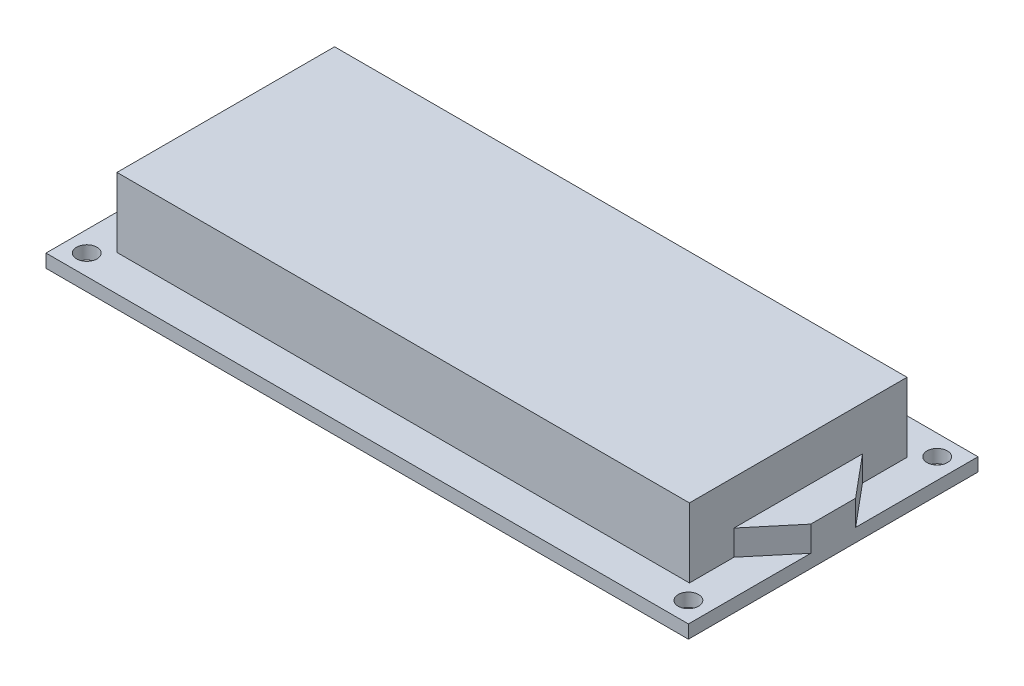
SolidWorks part; units mm, degrees
ref_plane "Front Plane" through (0, 0, 0) normal (0, 0, 1) x (1, 0, 0)
ref_plane "Top Plane" through (0, 0, 0) normal (0, 1, 0) x (1, 0, 0)
ref_plane "Right Plane" through (0, 0, 0) normal (1, 0, 0) x (0, 0, -1)
sketch "Sketch1" plane through (0, 0, 0) normal (0, 1, 0) x (1, 0, 0)
  line L1 (0, 14.1688) -> (80.01, 14.1688)
  line L2 (0, 14.1688) -> (0, 50.2368)
  line L3 (0, 50.2368) -> (80.01, 50.2368)
  line L4 (80.01, 14.1688) -> (80.01, 50.2368)
  dimension "D1" = 80.01
  dimension "D2" = 36.068
extrude "Boss-Extrude1" add sketch "Sketch1" along normal blind 1.651
sketch "Sketch2" plane through (0, 1.651, 0) normal (0, 1, 0) x (1, 0, 0)
  line L0 (0, 50.2368) -> (0, 14.1688) construction
  line L1 (80.01, 50.2368) -> (0, 50.2368) construction
  line L2 (0, 14.1688) -> (80.01, 14.1688) construction
  line L3 (80.01, 14.1688) -> (80.01, 50.2368) construction
  circle A0 centre (2.54, 47.6968) radius 1.27
  circle A1 centre (2.54, 16.7088) radius 1.27
  circle A2 centre (77.47, 47.6968) radius 1.27
  circle A3 centre (77.47, 16.7088) radius 1.27
  dimension "D1" = 2.54
  dimension "D2" = 2.54
  dimension "D3" = 2.54
  dimension "D4" = 2.54
  dimension "D5" = 2.54
extrude "Cut-Extrude1" cut sketch "Sketch2" against normal blind 2.54
sketch "Sketch3" plane through (0, 1.651, 0) normal (0, 1, 0) x (1, 0, 0)
  line L0 (80.01, 50.2368) -> (0, 50.2368) construction
  line L1 (4.3561, 45.7537) -> (75.6539, 45.7537)
  line L2 (4.3561, 45.7537) -> (4.3561, 18.6519)
  line L3 (4.3561, 18.6519) -> (75.6539, 18.6519)
  line L4 (75.6539, 45.7537) -> (75.6539, 18.6519)
  line L5 (0, 50.2368) -> (0, 14.1688) construction
  point P4 (40.005, 45.7537)
  point P7 (40.005, 50.2368)
  point P8 (4.3561, 32.2028)
  point P11 (0, 32.2028)
  dimension "D1" = 71.2978
  dimension "D2" = 27.1018
extrude "Boss-Extrude2" add sketch "Sketch3" along normal blind 8.636
sketch "Sketch4" plane through (0, 1.651, 0) normal (0, 1, 0) x (1, 0, 0)
  line L0 (4.3561, 40.2038) -> (0, 34.9968)
  line L1 (0, 34.9968) -> (0, 29.4088)
  line L2 (0, 29.4088) -> (4.3561, 24.2018)
  line L3 (4.3561, 24.2018) -> (4.3561, 40.2038)
  line L4 (4.3561, 45.7537) -> (4.3561, 18.6519) construction
  line L5 (0, 50.2368) -> (0, 14.1688) construction
  line L6 (0, 14.1688) -> (80.01, 14.1688) construction
  line L7 (4.3561, 40.2038) -> (4.3561, 50.2368) construction
  line L8 (4.3561, 24.2018) -> (4.3561, 14.1688) construction
  line L9 (80.01, 50.2368) -> (0, 50.2368) construction
  dimension "D1" = 10.033
  dimension "D2" = 5.588
extrude "Boss-Extrude3" add sketch "Sketch4" along normal blind 3.1496
ref_plane "midplane" through (40.005, 0, 0) normal (-1, 0, 0) x (0, 0, 1)
mirror "Mirror1" about plane through (40.005, 0, 0) normal (-1, 0, 0) of "Boss-Extrude3"
sketch "Sketch5" plane through (0, 0, 0) normal (0, -1, 0) x (1, 0, 0)
  line L0 (0, -50.2368) -> (0, -14.1688) construction
  line L1 (41.275, -18.9313) -> (44.45, -18.9313)
  line L2 (41.275, -18.9313) -> (41.275, -22.1063)
  line L3 (41.275, -22.1063) -> (44.45, -22.1063)
  line L4 (44.45, -18.9313) -> (44.45, -22.1063)
  line L5 (0, -14.1688) -> (80.01, -14.1688) construction
  dimension "D1" = 41.275
  dimension "D2" = 4.7625
  dimension "D3" = 3.175
  dimension "D4" = 3.175
extrude "Boss-Extrude4" add sketch "Sketch5" along normal blind 2.3813
